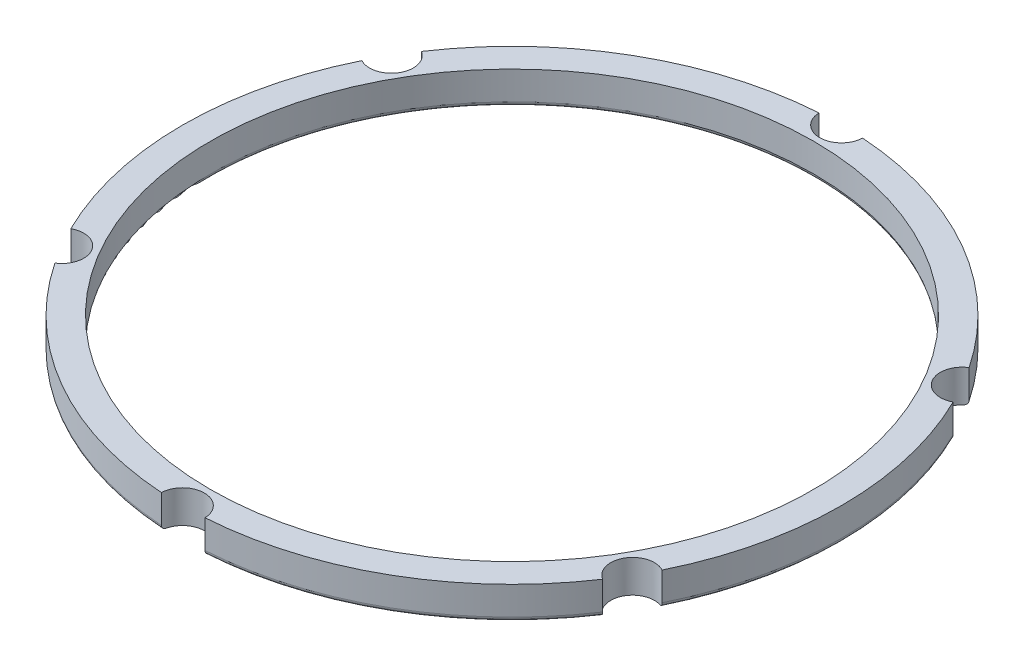
SolidWorks part; units mm, degrees
ref_plane "Спереди" through (0, 0, 0) normal (0, 0, 1) x (1, 0, 0)
ref_plane "Сверху" through (0, 0, 0) normal (0, 1, 0) x (1, 0, 0)
ref_plane "Справа" through (0, 0, 0) normal (1, 0, 0) x (0, 0, -1)
sketch "Эскиз1" plane through (0, 0, 0) normal (0, 1, 0) x (1, 0, 0)
  circle A0 centre (0, 0) radius 138.2111
  circle A1 centre (0, 0) radius 150.9875
extrude "Бобышка-Вытянуть1" add sketch "Эскиз1" along normal blind 15
fillet "Скругление1" radius 2 2 edges at (0, 0, 138.2111) (0, 0, 150.9875)
sketch "Эскиз2" plane through (0, 0, 0) normal (0, 1, 0) x (1, 0, 0)
  line L0 (0, 0) -> (0, 204.7044) construction
  circle A0 centre (0, 150.9875) radius 10
  circle A1 centre (0, 0) radius 150.9875 construction
  dimension "D1" = 20
  dimension "D2" = 204.7044
extrude "Вырез-Вытянуть1" cut sketch "Эскиз2" along normal blind 15 contours A0
pattern_circular "Круговой массив1" count 6 over 360 about axis through (0, 0, 0) along (0, 1, 0) of "Вырез-Вытянуть1"
